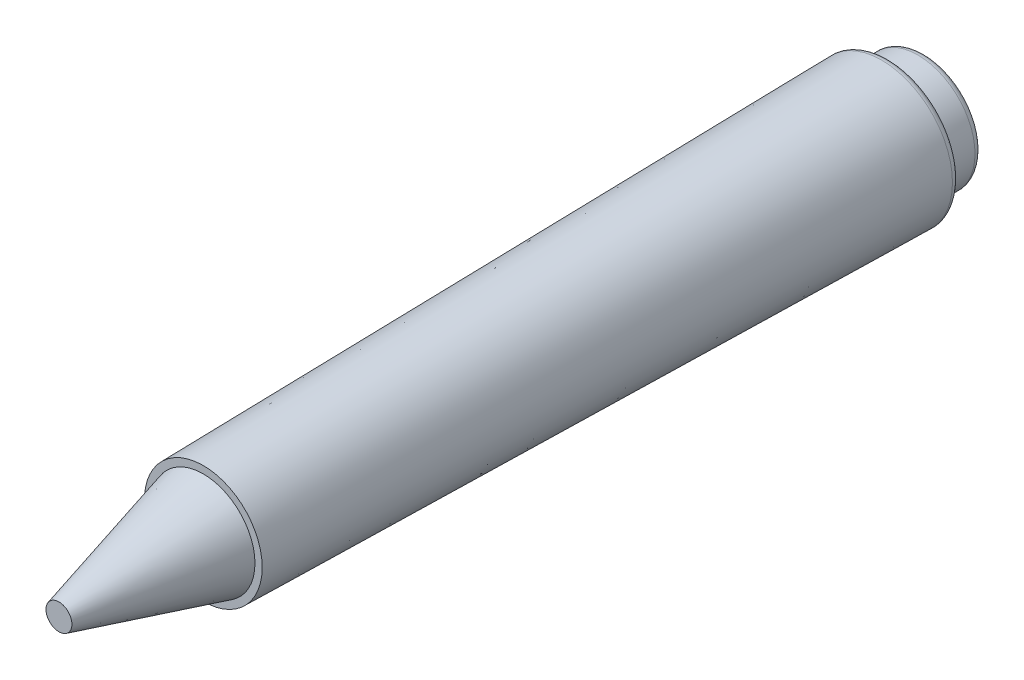
SolidWorks part; units mm, degrees
ref_plane "정면" through (0, 0, 0) normal (0, 0, 1) x (1, 0, 0)
ref_plane "윗면" through (0, 0, 0) normal (0, 1, 0) x (1, 0, 0)
ref_plane "우측면" through (0, 0, 0) normal (1, 0, 0) x (0, 0, -1)
sketch "스케치1" plane through (0, 0, 0) normal (0, 0, 1) x (1, 0, 0)
  circle A0 centre (0, 0) radius 9.9
  dimension "D1" = 19.8
extrude "보스-돌출1" add sketch "스케치1" along normal blind 100
draft "구배3" type of draft neutral plane draft angle 1 faces to draft 1 face at (9.9, 0, 100) neutral plane through (0, 0, 0) neutral plane normal (0, 0, -1) reverse direction yes parameters "D1"=1
sketch "스케치2" plane through (0, 0, 0) normal (0, 0, -1) x (-1, 0, 0)
  circle A1 centre (0, 0) radius 9.9
  circle A2 centre (0, 0) radius 7.9
  circle A3 centre (0, 0) radius 7.9
  dimension "D1" = 2
extrude "컷-돌출1" cut sketch "스케치2" against normal blind 5
fillet "필렛1" radius 1 1 edges at (-7.9, 0, 0)
fillet "필렛2" radius 1 1 edges at (-9.8127, 0, 5)
sketch "스케치5" plane through (0, 0, 100) normal (0, 0, 1) x (1, 0, 0)
  circle A2 centre (0, 0) radius 7.1545
  circle A3 centre (0, 0) radius 7.1545
  dimension "D1" = 1
extrude "보스-돌출3" add sketch "스케치5" along normal blind 20 separate body
draft "구배7" type of draft neutral plane draft angle 15 faces to draft 1 face at (7.1545, 0, 120) neutral plane through (0, 0, 100) neutral plane normal (0, 0, 1) parameters "D1"=15
